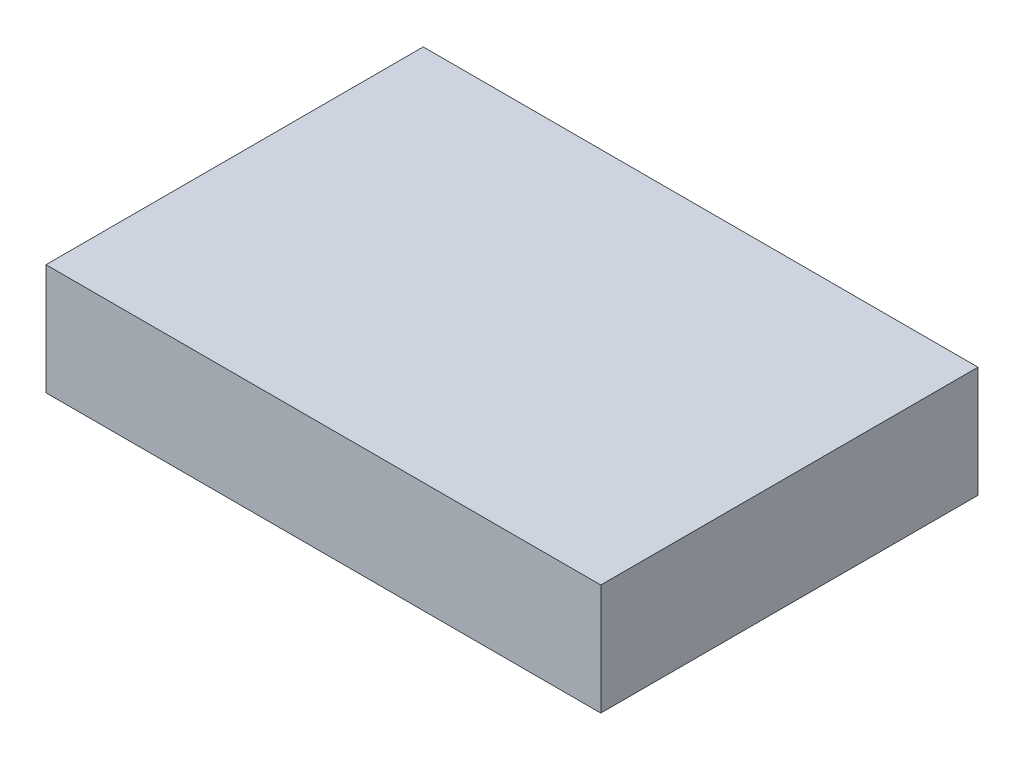
SolidWorks part; units mm, degrees
ref_plane "Front Plane" through (0, 0, 0) normal (0, 0, 1) x (1, 0, 0)
ref_plane "Top Plane" through (0, 0, 0) normal (0, 1, 0) x (1, 0, 0)
ref_plane "Right Plane" through (0, 0, 0) normal (1, 0, 0) x (0, 0, -1)
sketch "Sketch1" plane through (0, 0, 0) normal (0, 1, 0) x (1, 0, 0)
  line L1 (-25, 17) -> (25, 17)
  line L2 (-25, 17) -> (-25, -17)
  line L3 (-25, -17) -> (25, -17)
  line L4 (25, 17) -> (25, -17)
  line L5 (-25, 17) -> (25, -17) construction
  line L6 (-25, -17) -> (25, 17) construction
  point P0 (0, 0)
  dimension "D1" = 50
  dimension "D2" = 34
extrude "Boss-Extrude1" add sketch "Sketch1" along normal blind 10
